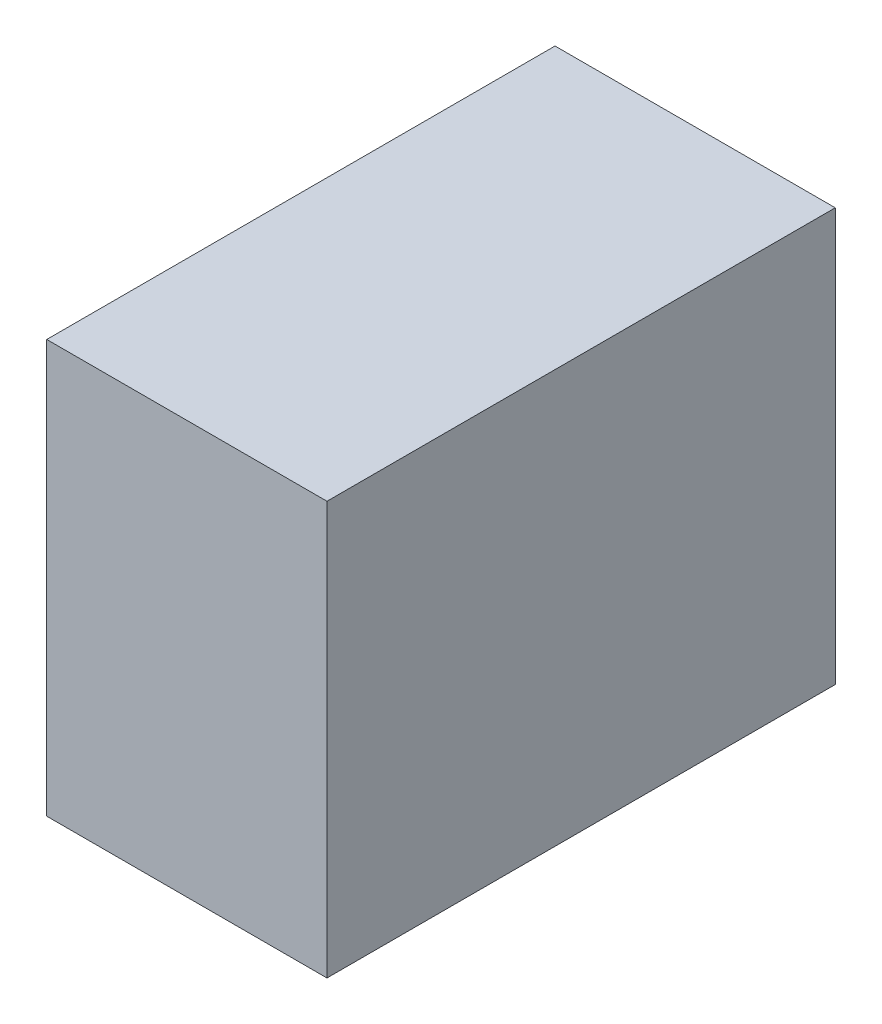
SolidWorks part; units mm, degrees
ref_plane "前视基准面" through (0, 0, 0) normal (0, 0, 1) x (1, 0, 0)
ref_plane "上视基准面" through (0, 0, 0) normal (0, 1, 0) x (1, 0, 0)
ref_plane "右视基准面" through (0, 0, 0) normal (1, 0, 0) x (0, 0, -1)
sketch "草图1" plane through (0, 0, 0) normal (1, 0, 0) x (0, 0, -1)
  line L0 (0, 0) -> (0, 55.4)
  line L1 (0, 55.4) -> (68.2, 55.4)
  line L2 (68.2, 55.4) -> (68.2, 0)
  line L3 (68.2, 0) -> (0, 0)
  dimension "D1" = 55.4
  dimension "D2" = 68.2
extrude "凸台-拉伸1" add sketch "草图1" along normal blind 37.6
